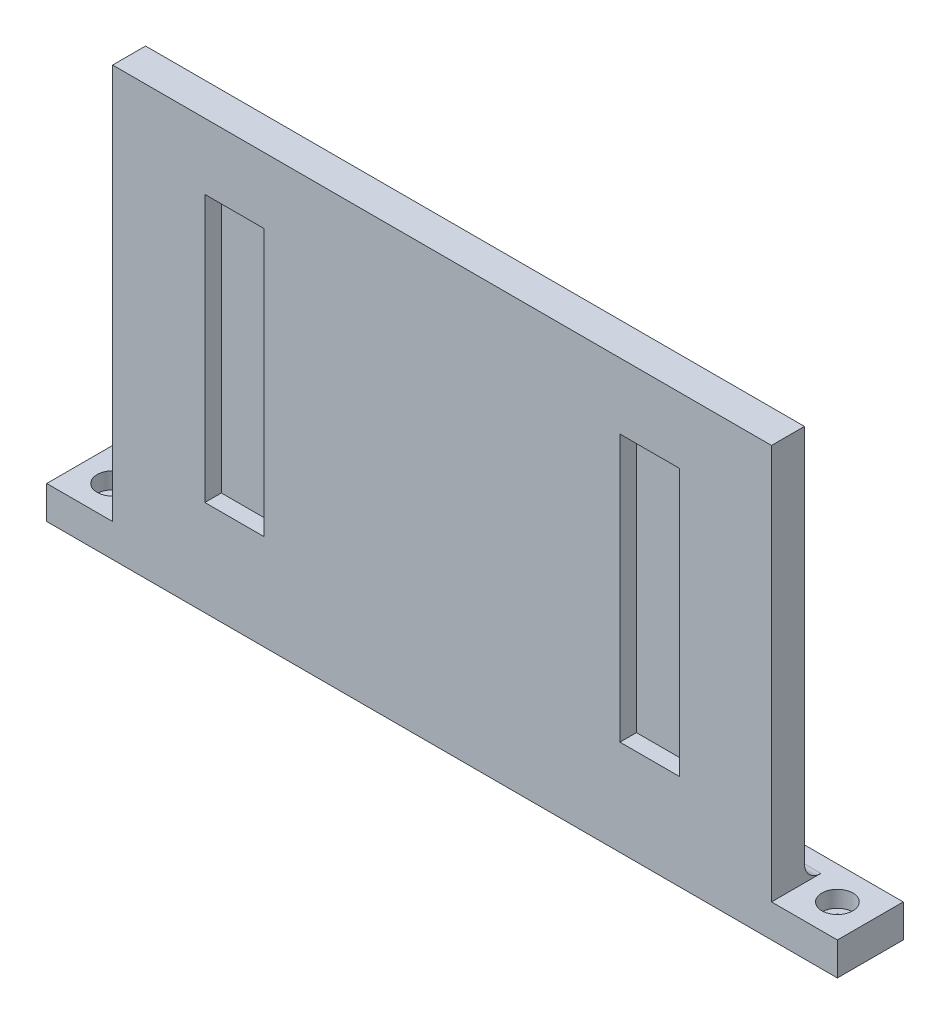
SolidWorks part; units mm, degrees
ref_plane "Front Plane" through (0, 0, 0) normal (0, 0, 1) x (1, 0, 0)
ref_plane "Top Plane" through (0, 0, 0) normal (0, 1, 0) x (1, 0, 0)
ref_plane "Right Plane" through (0, 0, 0) normal (1, 0, 0) x (0, 0, -1)
sketch "Sketch1" plane through (0, 0, 0) normal (0, 0, 1) x (1, 0, 0)
  line L0 (0, 0) -> (240, 0)
  line L1 (240, 0) -> (240, 10)
  line L2 (240, 10) -> (220, 10)
  line L3 (220, 10) -> (220, 130)
  line L4 (220, 130) -> (20, 130)
  line L5 (20, 130) -> (20, 10)
  line L6 (20, 10) -> (0, 10)
  line L7 (0, 10) -> (0, 0)
  dimension "D1" = 20
  dimension "D2" = 10
  dimension "D3" = 20
  dimension "D4" = 10
  dimension "D5" = 120
  dimension "D6" = 200
extrude "Boss-Extrude2" add sketch "Sketch1" along normal blind 20
sketch "Sketch2" plane through (0, 10, 0) normal (0, 1, 0) x (1, 0, 0)
  line L0 (0, -20) -> (0, 0) construction
  line L1 (20, -20) -> (0, -20) construction
  line L2 (240, 0) -> (220, 0) construction
  line L3 (240, -20) -> (240, 0) construction
  circle A0 centre (10, -10) radius 3
  circle A1 centre (230, -10) radius 3
  dimension "D1" = 6
  dimension "D4" = 6
  dimension "D2" = 10
  dimension "D3" = 10
  dimension "D5" = 10
  dimension "D6" = 10
extrude "Cut-Extrude1" cut sketch "Sketch2" against normal blind 20
sketch "Sketch3" plane through (0, 0, 0) normal (0, 0, -1) x (-1, 0, 0)
  line L1 (-220, 130) -> (-20, 130)
  line L2 (-220, 130) -> (-220, 10)
  line L3 (-220, 10) -> (-20, 10)
  line L4 (-20, 130) -> (-20, 10)
extrude "Cut-Extrude2" cut sketch "Sketch3" against normal blind 10
sketch "Sketch4" plane through (0, 0, 20) normal (0, 0, 1) x (1, 0, 0)
  line L1 (48, 110) -> (66, 110)
  line L2 (48, 110) -> (48, 29)
  line L3 (48, 29) -> (66, 29)
  line L4 (66, 110) -> (66, 29)
  line L5 (174, 110) -> (192, 110)
  line L6 (174, 110) -> (174, 29)
  line L7 (174, 29) -> (192, 29)
  line L8 (192, 110) -> (192, 29)
  line L9 (20, 130) -> (20, 10) construction
  line L11 (220, 130) -> (20, 130) construction
  point P8 (57, 110)
  dimension "D1" = 108
  dimension "D2" = 46
  dimension "D3" = 18
  dimension "D4" = 18
  dimension "D5" = 81
  dimension "D6" = 81
  dimension "D7" = 20
  dimension "D8" = 20
fillet "Fillet1" radius 5 1 edges at (120, 10, 10)
sketch "Sketch6" plane through (0, 0, 0) normal (0, -1, 0) x (1, 0, 0)
  circle A1 centre (10, 10) radius 3
  circle A2 centre (10, 10) radius 2.5
  circle A3 centre (230, 10) radius 3
  circle A4 centre (230, 10) radius 2.5
  dimension "D1" = 5
  dimension "D2" = 5
extrude "Boss-Extrude3" add sketch "Sketch6" against normal up to surface (10 mm away) up to face at (7, 10, 10)
sketch "Sketch7" plane through (0, 10, 0) normal (0, 1, 0) x (1, 0, 0)
  circle A0 centre (230, -10) radius 4.7
  circle A1 centre (10, -10) radius 4.7
  dimension "D1" = 9.4
  dimension "D2" = 9.4
extrude "Cut-Extrude6" cut sketch "Sketch7" against normal blind 5
extrude "Cut-Extrude7" cut sketch "Sketch4" against normal blind 5
